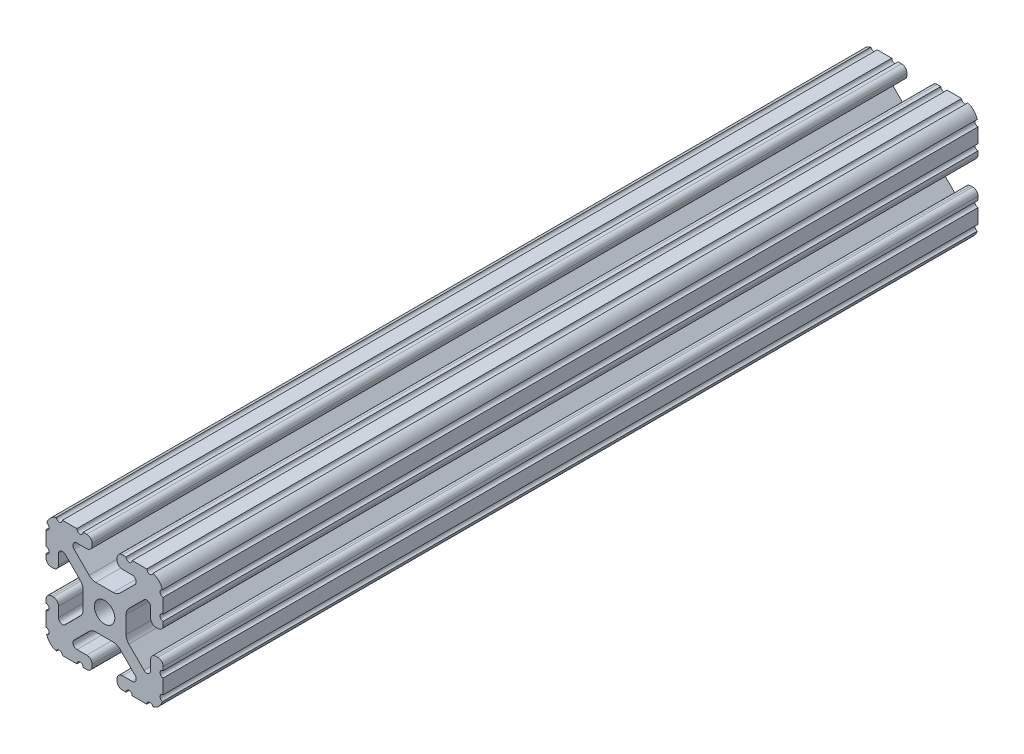
SolidWorks part; units mm, degrees
ref_plane "Front Plane" through (0, 0, 0) normal (0, 0, 1) x (1, 0, 0)
ref_plane "Top Plane" through (0, 0, 0) normal (0, 1, 0) x (1, 0, 0)
ref_plane "Right Plane" through (0, 0, 0) normal (1, 0, 0) x (0, 0, -1)
sketch "Sketch2" plane through (0, 0, 0) normal (0, 0, 1) x (1, 0, 0)
  line L0 (0, 19.05) -> (0, -19.05) construction
  line L1 (-19.05, 0) -> (19.05, 0) construction
  line L2 (4.064, -19.05) -> (19.05, -19.05)
  line L3 (19.05, -19.05) -> (19.05, -4.064)
  line L4 (4.064, -19.05) -> (4.064, -14.986)
  line L5 (4.064, -14.986) -> (12.1123, -14.986)
  line L6 (12.1123, -14.986) -> (4.1113, -6.985)
  line L7 (0, 0) -> (19.05, -19.05) construction
  line L8 (19.05, -4.064) -> (14.986, -4.064)
  line L9 (14.986, -4.064) -> (14.986, -12.1123)
  line L10 (14.986, -12.1123) -> (6.985, -4.1113)
  circle A0 centre (0, 0) radius 3.3274
  arc A1 (8.9963, -14.986) -> (9.909, -12.7826) centre (8.9963, -13.6953) ccw construction
  point P8 (0, -6.985)
  dimension "Center Hole Diameter" = 6.6548
  dimension "Rail Height" = 38.1
  dimension "Rail Width" = 38.1
  dimension "T-Slot Width" = 8.128
  dimension "Slot Inner Width" = 20.574
  dimension "Thickness" = 4.064
  dimension "Slot Depth" = 8.001
  dimension "D1" = 4.064
sketch "Sketch3" plane through (0, 0, 0) normal (1, 0, 0) x (0, 0, -1)
  line L0 (-132.5, -19.05) -> (132.5, -19.05) construction
  line L1 (-107.1, 0) -> (107.1, 0) construction
  dimension "Length" = 265
  dimension "D1" = 25.4
sketch "Sketch4" plane through (0, 0, 0) normal (0, 0, 1) x (1, 0, 0)
  line L0 (5.7912, -19.05) -> (14.3002, -19.05)
  line L1 (4.064, -19.05) -> (19.05, -19.05) construction
  line L2 (4.064, -19.05) -> (4.064, -14.986) construction
  line L3 (4.064, -14.986) -> (12.1123, -14.986) construction
  line L4 (4.064, -16.7132) -> (4.064, -17.3228)
  line L5 (5.7912, -14.986) -> (8.9963, -14.986)
  line L6 (0, -6.985) -> (2.833, -6.985)
  line L7 (12.1123, -14.986) -> (4.1113, -6.985) construction
  line L8 (5.0152, -7.8889) -> (9.909, -12.7826)
  line L9 (19.05, -19.05) -> (19.05, -4.064) construction
  line L10 (14.986, -12.1123) -> (6.985, -4.1113) construction
  line L11 (14.986, -4.064) -> (14.986, -12.1123) construction
  line L12 (14.986, -8.9963) -> (14.986, -5.7912)
  line L13 (19.05, -4.064) -> (14.986, -4.064) construction
  line L14 (16.7132, -4.064) -> (17.3228, -4.064)
  line L15 (19.05, -5.7912) -> (19.05, -14.3002)
  line L16 (12.7826, -9.909) -> (7.8889, -5.0152)
  line L17 (6.985, 0) -> (6.985, -2.833)
  line L18 (-19.05, 0) -> (19.05, 0) construction
  line L19 (0, -6.985) -> (0, -3.3274)
  line L20 (0, 19.05) -> (0, -19.05) construction
  line L21 (6.985, 0) -> (3.3274, 0)
  arc A0 (4.064, -17.3228) -> (5.7912, -19.05) centre (5.7912, -17.3228) ccw
  arc A2 (4.064, -16.7132) -> (5.7912, -14.986) centre (5.7912, -16.7132) cw
  arc A3 (8.9963, -14.986) -> (9.909, -12.7826) centre (8.9963, -13.6953) ccw
  arc A4 (2.833, -6.985) -> (5.0152, -7.8889) centre (2.833, -10.0711) cw
  arc A5 (14.3002, -19.05) -> (19.05, -14.3002) centre (14.3002, -14.3002) ccw
  arc A6 (12.7826, -9.909) -> (14.986, -8.9963) centre (13.6953, -8.9963) ccw
  arc A7 (14.986, -5.7912) -> (16.7132, -4.064) centre (16.7132, -5.7912) cw
  arc A8 (17.3228, -4.064) -> (19.05, -5.7912) centre (17.3228, -5.7912) cw
  arc A9 (7.8889, -5.0152) -> (6.985, -2.833) centre (10.0711, -2.833) cw
  circle A10 centre (0, 0) radius 3.3274 construction
  arc A11 (0, -3.3274) -> (3.3274, 0) centre (0, 0) ccw
  dimension "D1" = 4.7498
  dimension "D2" = 3.0861
  dimension "D3" = 1.7272
extrude "Boss-Extrude1" add sketch "Sketch4" along normal mid plane 265
sketch "Sketch5" plane through (0, 0, 0) normal (0, 0, 1) x (1, 0, 0)
  line L0 (4.064, -19.05) -> (19.05, -19.05) construction
  line L1 (5.7912, -14.986) -> (8.9963, -14.986) construction
  line L3 (0, 0) -> (19.05, -19.05) construction
  line L4 (8.9963, -14.986) -> (8.9963, -19.05) construction
  line L5 (12.1123, -14.986) -> (4.1113, -6.985) construction
  circle A0 centre (14.7395, -19.05) radius 1.016
  circle A1 centre (7.9803, -19.05) radius 1.016
  circle A2 centre (19.05, -14.7395) radius 1.016
  circle A3 centre (19.05, -7.9803) radius 1.016
  point P10 (7.3938, -14.986)
  point P12 (13.6953, -8.9963)
  dimension "D1" = 2.032
extrude "Cut-Extrude1" cut sketch "Sketch5" against normal through all both and the other way through all
mirror "Mirror1" about plane through (0, 0, 0) normal (1, 0, 0) of bodies 137 134
mirror "Mirror2" about plane through (0, 0, 0) normal (0, 1, 0) of bodies 135
equation "\"D1@Boss-Extrude1\"=\"Length@Sketch3\""
equation "\"D1@Sketch2\"=\"Thickness@Sketch2\""
equation "\"D2@Sketch4\"=\"Slot Inner Width@Sketch2\"*0.15"
equation "\"D1@Sketch4\"=\"D3@Sketch4\"*2.75"
equation "\"D3@Sketch4\"=\"Thickness@Sketch2\"*0.425"
equation "\"D1@Sketch5\"=\"Thickness@Sketch2\"*0.5"
